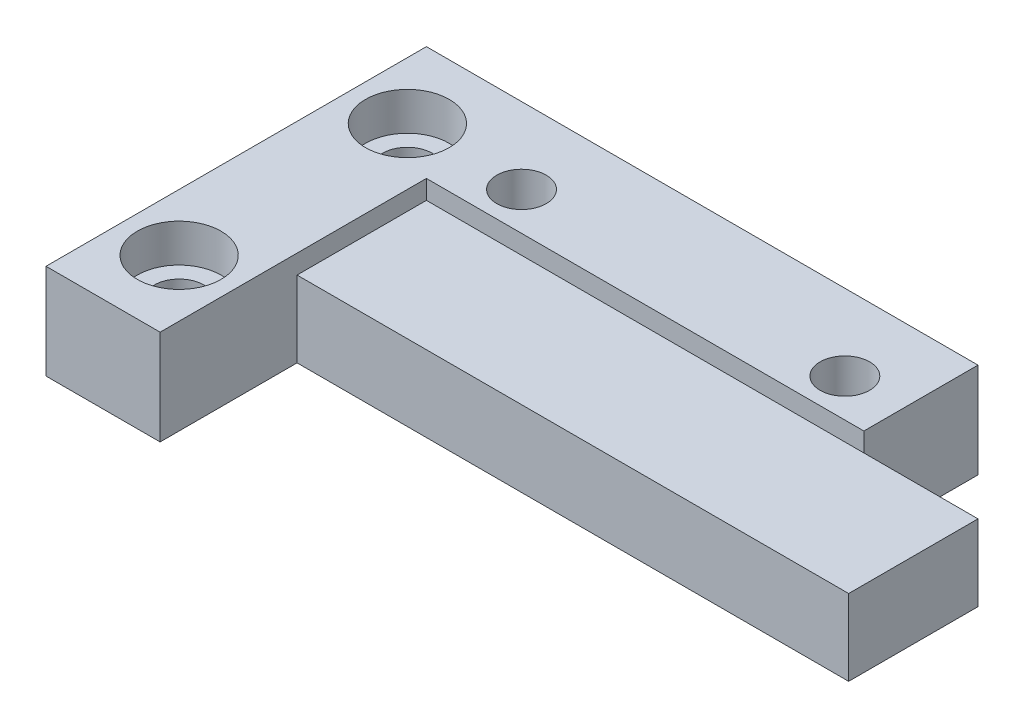
SolidWorks part; units mm, degrees
ref_plane "前基準面" through (0, 0, 0) normal (0, 0, 1) x (1, 0, 0)
ref_plane "上基準面" through (0, 0, 0) normal (0, 1, 0) x (1, 0, 0)
ref_plane "右基準面" through (0, 0, 0) normal (1, 0, 0) x (0, 0, -1)
sketch "草圖1" plane through (0, 0, 0) normal (0, 1, 0) x (1, 0, 0)
  line L1 (0, 0) -> (35, 0)
  line L2 (0, 0) -> (0, 20)
  line L3 (0, 20) -> (35, 20)
  line L4 (35, 0) -> (35, 20)
  dimension "D1" = 35
  dimension "D2" = 20
extrude "填料-伸長1" add sketch "草圖1" along normal blind 5
sketch "草圖2" plane through (0, 0, 0) normal (0, 1, 0) x (1, 0, 0)
  line L0 (0, 20) -> (0, 0) construction
  line L1 (6, 0) -> (35, 0)
  line L2 (6, 0) -> (6, 14)
  line L3 (6, 14) -> (35, 14)
  line L4 (35, 0) -> (35, 14)
  dimension "D1" = 29
  dimension "D2" = 14
  dimension "D3" = 6
  dimension "D4" = 14
extrude "除料-伸長2" cut sketch "草圖2" along normal blind 1
sketch "草圖3" plane through (0, 0, 0) normal (0, 1, 0) x (1, 0, 0)
  line L1 (6, 0) -> (35, 0)
  line L2 (6, 0) -> (6, 7.2)
  line L3 (6, 7.2) -> (35, 7.2)
  line L4 (35, 0) -> (35, 7.2)
  dimension "D1" = 29
  dimension "D2" = 7.2
extrude "除料-伸長4" cut sketch "草圖3" along normal through all
sketch "草圖4" plane through (0, 0, 0) normal (0, 1, 0) x (1, 0, 0)
  line L1 (35, 20) -> (29, 20)
  line L2 (35, 20) -> (35, 14)
  line L3 (35, 14) -> (29, 14)
  line L4 (29, 20) -> (29, 14)
  dimension "D1" = 6
  dimension "D2" = 6
extrude "除料-伸長5" cut sketch "草圖4" along normal through all
sketch "草圖5" plane through (0, 0, 0) normal (0, 1, 0) x (1, 0, 0)
  circle A0 centre (3, 16) radius 1.3
  circle A1 centre (3, 4) radius 1.3
  circle A2 centre (9, 16) radius 1.3
  circle A4 centre (26, 16) radius 1.3
extrude "除料-伸長6" cut sketch "草圖5" along normal through all
sketch "草圖7" plane through (0, 0, 0) normal (0, 1, 0) x (1, 0, 0)
  line L1 (26, 18.4) -> (23.9215, 17.2)
  line L2 (23.9215, 17.2) -> (23.9215, 14.8)
  line L3 (23.9215, 14.8) -> (26, 13.6)
  line L4 (26, 13.6) -> (28.0785, 14.8)
  line L5 (28.0785, 14.8) -> (28.0785, 17.2)
  line L6 (28.0785, 17.2) -> (26, 18.4)
  line L8 (9, 18.4) -> (6.9215, 17.2)
  line L9 (6.9215, 17.2) -> (6.9215, 14.8)
  line L10 (6.9215, 14.8) -> (9, 13.6)
  line L11 (9, 13.6) -> (11.0785, 14.8)
  line L12 (11.0785, 14.8) -> (11.0785, 17.2)
  line L13 (11.0785, 17.2) -> (9, 18.4)
  circle A0 centre (9, 16) radius 2.0785 construction
  circle A1 centre (26, 16) radius 2.0785 construction
  dimension "D1" = 4.8
  dimension "D2" = 4.8
extrude "除料-伸長8" cut sketch "草圖7" against normal blind 2.3 from surface at 5 starting at face at (9, 5, -14.7)
sketch "草圖6" plane through (0, 0, 0) normal (0, 1, 0) x (1, 0, 0)
  circle A1 centre (3, 16) radius 2.2
  circle A2 centre (3, 4) radius 2.2
extrude "除料-伸長10" cut sketch "草圖6" along normal blind 2 from surface at 0 starting at face at (9, 0, -14.7)
mirror "鏡射4" about plane through (0, 5, 0) normal (0, -1, 0) of "除料-伸長10", "除料-伸長8", "除料-伸長6", "除料-伸長5", "除料-伸長4", "除料-伸長2", "填料-伸長1"
sketch "草圖8" plane through (0, 0, 0) normal (0, 1, 0) x (1, 0, 0)
  line L1 (0, 0) -> (36.682, 0)
  line L2 (0, 0) -> (0, 21.2848)
  line L3 (0, 21.2848) -> (36.682, 21.2848)
  line L4 (36.682, 0) -> (36.682, 21.2848)
extrude "除料-伸長11" cut sketch "草圖8" along normal blind 5
